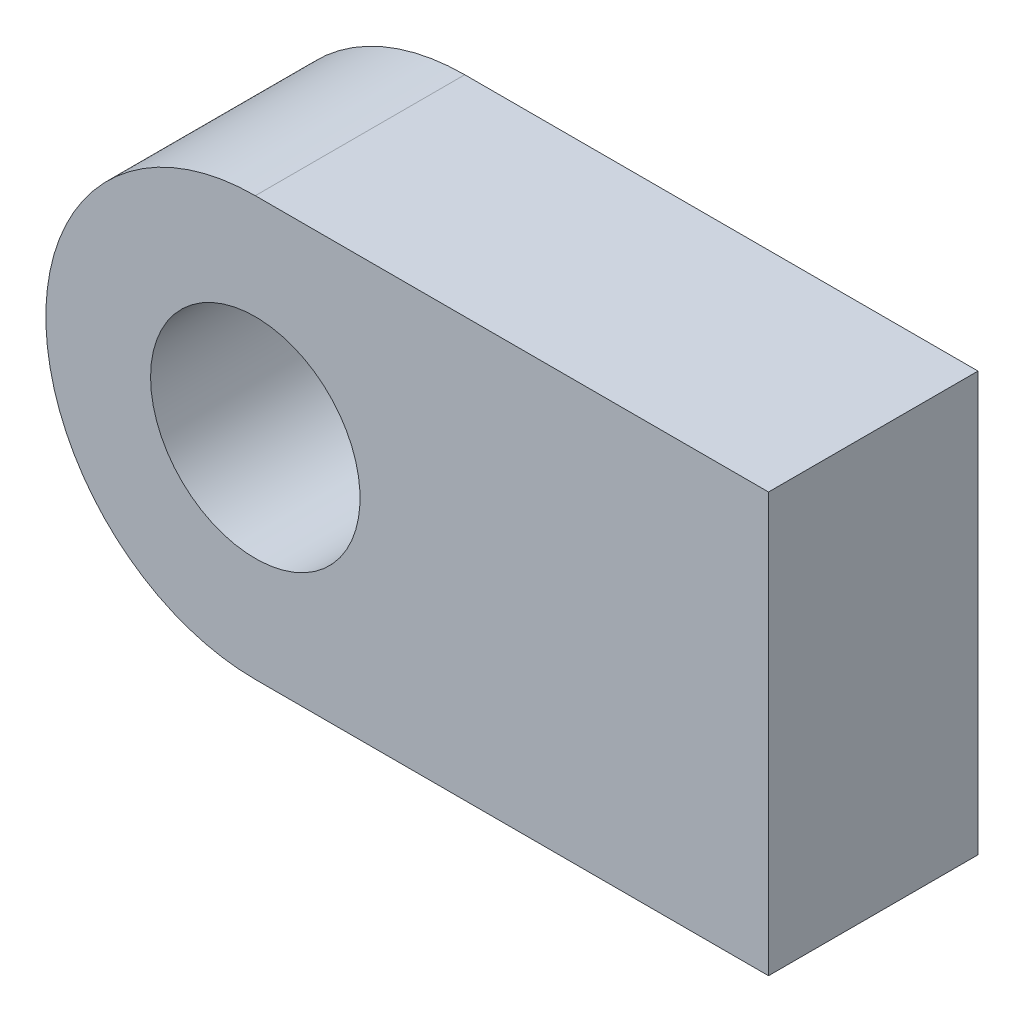
SolidWorks part; units mm, degrees
material "AISI 4130 Steel, normalized at 870C"
ref_plane "Front Plane" through (0, 0, 0) normal (0, 0, 1) x (1, 0, 0)
ref_plane "Top Plane" through (0, 0, 0) normal (0, 1, 0) x (1, 0, 0)
ref_plane "Right Plane" through (0, 0, 0) normal (1, 0, 0) x (0, 0, -1)
sketch "Sketch7" plane through (0, 0, 0) normal (0, 1, 0) x (1, 0, 0)
  line L0 (0, -5) -> (34.5, -5)
  line L1 (34.5, -5) -> (34.5, 5)
  line L2 (34.5, 5) -> (0, 5)
  line L4 (0, 5) -> (0, -5)
  point P2 (0, 0)
  dimension "D2" = 10
  dimension "D3" = 34.5
extrude "Boss-Extrude3" add sketch "Sketch7" along normal blind 20
sketch "Sketch8" plane through (0, 0, -5) normal (0, 0, -1) x (-1, 0, 0)
  line L1 (-34.5, 20) -> (0, 20) construction
  line L2 (-34.5, 0) -> (0, 0) construction
  line L3 (0, 20) -> (0, 0) construction
  line L6 (-10, 20) -> (6.2691, 20)
  line L7 (6.2691, 20) -> (6.2691, 0)
  line L8 (6.2691, 0) -> (-10, 0)
  arc A0 (-10, 20) -> (-10, 0) centre (-10, 10) cw
  point P9 (0, 10)
  point P12 (0, 10)
extrude "Cut-Extrude9" cut sketch "Sketch8" against normal blind 26
sketch "Sketch9" plane through (0, 0, -5) normal (0, 0, -1) x (-1, 0, 0)
  circle A0 centre (-10, 10) radius 5
  dimension "D1" = 10
extrude "Cut-Extrude10" cut sketch "Sketch9" against normal blind 26
